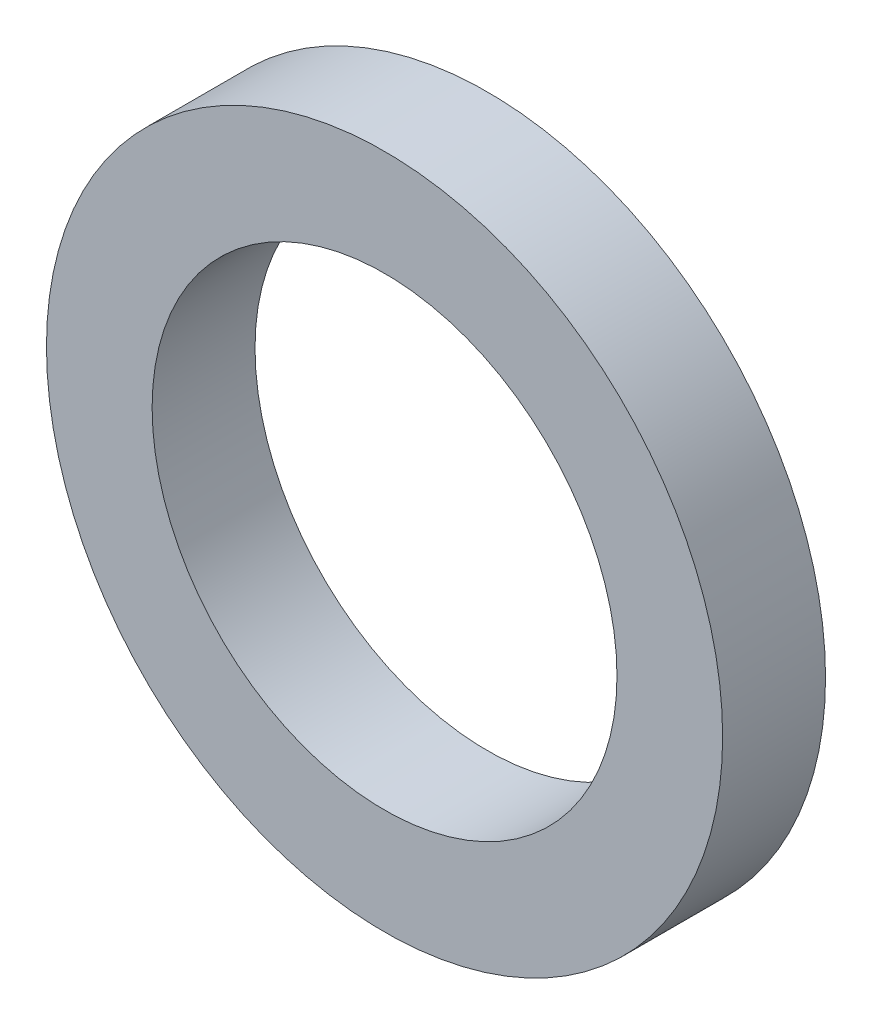
SolidWorks part; units mm, degrees
ref_plane "Front" through (0, 0, 0) normal (0, 0, 1) x (1, 0, 0)
ref_plane "Top" through (0, 0, 0) normal (0, 1, 0) x (1, 0, 0)
ref_plane "Right" through (0, 0, 0) normal (1, 0, 0) x (0, 0, -1)
sketch "Sketch1" plane through (0, 0, 0) normal (0, 0, 1) x (1, 0, 0)
  circle A0 centre (0, 0) radius 6.325
  circle A1 centre (0, 0) radius 9.2
extrude "Boss-Extrude1" add sketch "Sketch1" along normal blind 2.8
